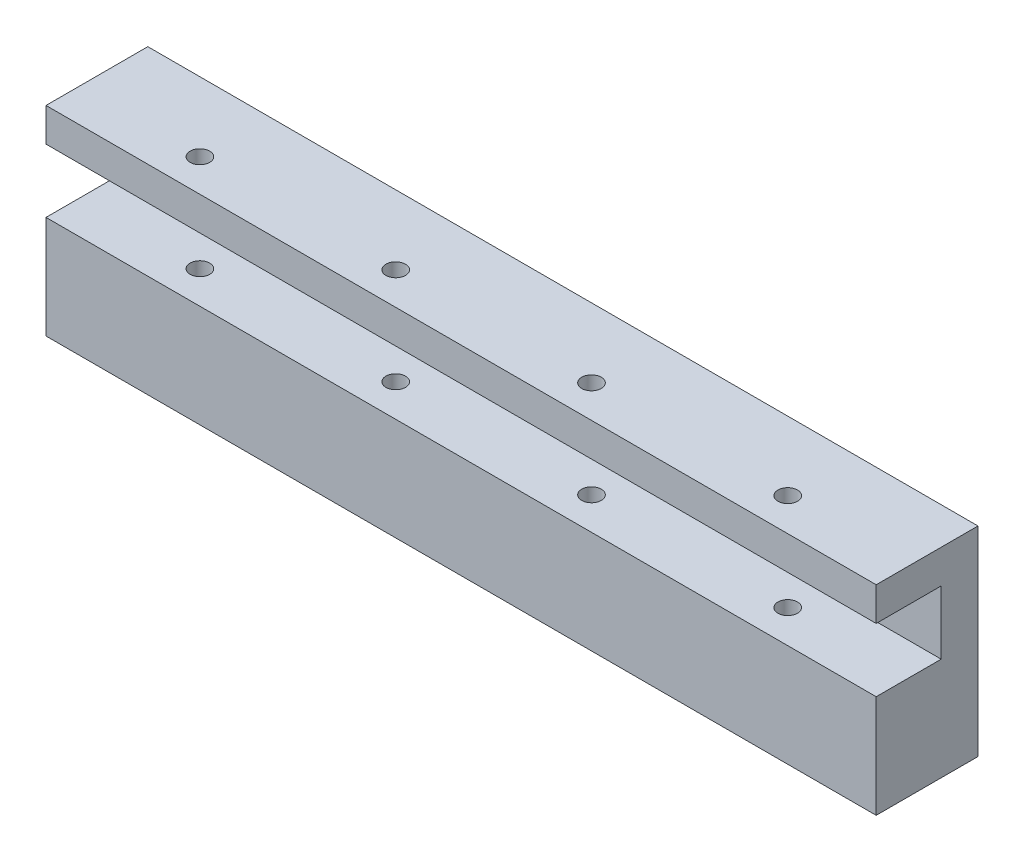
SolidWorks part; units mm, degrees
ref_plane "Front Plane" through (0, 0, 0) normal (0, 0, 1) x (1, 0, 0)
ref_plane "Top Plane" through (0, 0, 0) normal (0, 1, 0) x (1, 0, 0)
ref_plane "Right Plane" through (0, 0, 0) normal (1, 0, 0) x (0, 0, -1)
sketch "Sketch4" plane through (0, 0, 0) normal (0, 0, 1) x (1, 0, 0)
  line L1 (-89.891, -16.65) -> (16.109, -16.65)
  line L2 (-89.891, -16.65) -> (-89.891, -42.15)
  line L3 (-89.891, -42.15) -> (16.109, -42.15)
  line L4 (16.109, -16.65) -> (16.109, -42.15)
  dimension "D1" = 25.5
  dimension "D2" = 106
extrude "Boss-Extrude2" add sketch "Sketch4" against normal blind 13
sketch "Sketch25" plane through (0, 0, 0) normal (0, 0, 1) x (1, 0, 0)
  line L0 (-89.891, -16.65) -> (-89.891, -42.15) construction
  line L1 (-89.891, -20.93) -> (16.109, -20.93)
  line L2 (-89.891, -20.93) -> (-89.891, -29.03)
  line L3 (-89.891, -29.03) -> (16.109, -29.03)
  line L4 (16.109, -20.93) -> (16.109, -29.03)
  line L5 (16.109, -42.15) -> (16.109, -16.65) construction
  dimension "D1" = 4.28
  dimension "D2" = 13.12
  dimension "D3" = 8.1
extrude "Cut-Extrude3" cut sketch "Sketch25" against normal blind 8.3 and the other way through all
hole_wizard "M3x0.5 Tapped Hole1" positions "3DSketch1" profile "Sketch27" tap size "M3x0.5" standard "ANSI Metric" end condition through all
sketch3d "3DSketch1"
  line L0 (16.109, -16.65, -13) -> (16.109, -16.65, 0) construction
  line L2 (16.109, -16.65, 0) -> (-89.891, -16.65, 0) construction
  line L3 (-89.891, -16.65, -13) -> (-89.891, -16.65, 0) construction
  point P0 (-74.391, -16.65, -4.15)
  point P2 (-49.391, -16.65, -4.15)
  point P4 (0.609, -16.65, -4.2057)
  point P6 (-24.391, -16.65, -4.15)
  dimension "D1" = 15.5
  dimension "D2" = 25
  dimension "D5" = 4.15
  dimension "D6" = 4.15
  dimension "D7" = 4.15
  dimension "D8" = 25
  dimension "D9" = 25
  dimension "D10" = 15.5001
cosmetic thread "Hole Thread2" parameters "D1"=6, "D2"=3
cosmetic thread "Hole Thread3" parameters "D1"=6, "D2"=3
cosmetic thread "Hole Thread4" parameters "D1"=6, "D2"=3
cosmetic thread "Hole Thread5" parameters "D1"=6, "D2"=3
sketch "Sketch27" plane through (-74.391, -16.65, -4.15) normal (1, 0, 0) x (0, 0, 1)
  line L0 (0, 0) -> (0, 25.5)
  line L1 (0, 25.5) -> (1.25, 25.5)
  line L2 (1.25, 25.5) -> (1.25, 0)
  line L5 (1.25, 0) -> (0, 0)
  line L11 (0, -6.35) -> (0, 107.95) construction
  dimension "Thru Tap Drill Dia." = 2.5
  dimension "Thru Tap Drill Depth" = 25.5
